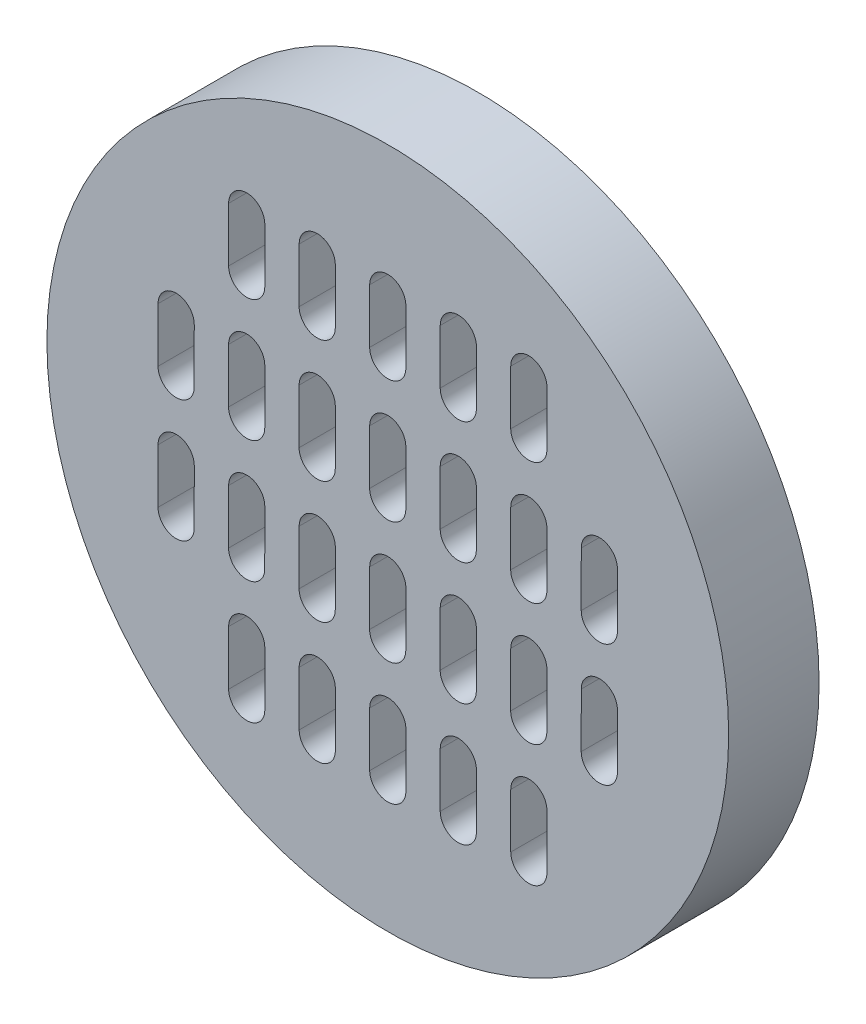
SolidWorks part; units mm, degrees
ref_plane "Спереди" through (0, 0, 0) normal (0, 0, 1) x (1, 0, 0)
ref_plane "Сверху" through (0, 0, 0) normal (0, 1, 0) x (1, 0, 0)
ref_plane "Справа" through (0, 0, 0) normal (1, 0, 0) x (0, 0, -1)
sketch "Sketch1" plane through (0, 0, 0) normal (0, 0, 1) x (1, 0, 0)
  line L0 (3.9, 6.755) -> (7.8, 0) construction
  line L2 (5.85, 10.1325) -> (11.7, 0) construction
  line L4 (7.8, 13.51) -> (15.6, 0) construction
  circle A61 centre (0, 0) radius 20
  circle A131 centre (0, 0) radius 1.25
  circle A484 centre (3.9, 0) radius 1.25
  circle A485 centre (7.8, 0) radius 1.25
  circle A486 centre (11.7, 0) radius 1.25
  circle A487 centre (15.6, 0) radius 1.25
  circle A488 centre (1.95, -3.3775) radius 1.25
  circle A489 centre (3.9, -6.755) radius 1.25
  circle A490 centre (5.85, -10.1325) radius 1.25
  circle A491 centre (7.8, -13.51) radius 1.25
  circle A492 centre (-1.95, -3.3775) radius 1.25
  circle A493 centre (-3.9, -6.755) radius 1.25
  circle A494 centre (-5.85, -10.1325) radius 1.25
  circle A495 centre (-7.8, -13.51) radius 1.25
  circle A496 centre (-3.9, 0) radius 1.25
  circle A497 centre (-7.8, 0) radius 1.25
  circle A498 centre (-11.7, 0) radius 1.25
  circle A499 centre (-15.6, 0) radius 1.25
  circle A500 centre (-1.95, 3.3775) radius 1.25
  circle A501 centre (-3.9, 6.755) radius 1.25
  circle A502 centre (-5.85, 10.1325) radius 1.25
  circle A503 centre (-7.8, 13.51) radius 1.25
  circle A504 centre (1.95, 3.3775) radius 1.25
  circle A505 centre (3.9, 6.755) radius 1.25
  circle A506 centre (5.85, 10.1325) radius 1.25
  circle A507 centre (7.8, 13.51) radius 1.25
  circle A508 centre (5.85, 3.3775) radius 1.25
  circle A509 centre (7.8, 6.755) radius 1.25
  circle A510 centre (9.75, 3.3775) radius 1.25
  circle A511 centre (11.7, 6.755) radius 1.25
  circle A512 centre (9.7491, 10.1341) radius 1.25
  circle A513 centre (13.6509, 3.3759) radius 1.25
  circle A514 centre (5.85, -3.3791) radius 1.25
  circle A515 centre (9.75, -3.3791) radius 1.25
  circle A516 centre (7.8, -6.7566) radius 1.25
  circle A517 centre (11.7, -6.7566) radius 1.25
  circle A518 centre (9.7491, -10.1356) radius 1.25
  circle A519 centre (13.6509, -3.3775) radius 1.25
  circle A520 centre (-0.0013, -6.7573) radius 1.25
  circle A521 centre (1.9487, -10.1348) radius 1.25
  circle A522 centre (-1.9513, -10.1348) radius 1.25
  circle A523 centre (-0.0013, -13.5123) radius 1.25
  circle A524 centre (-3.9032, -13.5123) radius 1.25
  circle A525 centre (3.9005, -13.5123) radius 1.25
  circle A526 centre (-5.8527, -3.3791) radius 1.25
  circle A527 centre (-7.8027, -6.7566) radius 1.25
  circle A528 centre (-9.7527, -3.3791) radius 1.25
  circle A529 centre (-11.7027, -6.7566) radius 1.25
  circle A530 centre (-13.6536, -3.3775) radius 1.25
  circle A531 centre (-9.7518, -10.1356) radius 1.25
  circle A532 centre (-5.8527, 3.3775) radius 1.25
  circle A533 centre (-9.7527, 3.3775) radius 1.25
  circle A534 centre (-7.8027, 6.755) radius 1.25
  circle A535 centre (-11.7027, 6.755) radius 1.25
  circle A536 centre (-9.7518, 10.1341) radius 1.25
  circle A537 centre (-13.6536, 3.3759) radius 1.25
  circle A538 centre (-0.0014, 6.7558) radius 1.25
  circle A539 centre (-1.9514, 10.1333) radius 1.25
  circle A540 centre (1.9486, 10.1333) radius 1.25
  circle A541 centre (-0.0014, 13.5108) radius 1.25
  circle A542 centre (3.9005, 13.5108) radius 1.25
  circle A543 centre (-3.9032, 13.5108) radius 1.25
  circle A544 centre (13.65, -1.1258) radius 2.2517 construction
  circle A545 centre (11.7009, -4.5044) radius 2.2522 construction
  circle A546 centre (9.75, -7.8834) radius 2.2522 construction
  circle A547 centre (7.7987, -11.2591) radius 2.2509 construction
  circle A548 centre (13.65, -1.1258) radius 0.65
  circle A549 centre (11.7009, -4.5044) radius 0.65
  circle A550 centre (9.75, -7.8834) radius 0.65
  circle A551 centre (7.7987, -11.2591) radius 0.65
  circle A552 centre (9.75, -1.1258) radius 0.65
  circle A553 centre (7.8009, -4.5044) radius 0.65
  circle A554 centre (5.85, -7.8834) radius 0.65
  circle A555 centre (3.8987, -11.2591) radius 0.65
  circle A556 centre (5.85, -1.1258) radius 0.65
  circle A557 centre (3.9009, -4.5044) radius 0.65
  circle A558 centre (1.95, -7.8834) radius 0.65
  circle A559 centre (-0.0013, -11.2591) radius 0.65
  circle A560 centre (1.95, -1.1258) radius 0.65
  circle A561 centre (0.0009, -4.5044) radius 0.65
  circle A562 centre (-1.95, -7.8834) radius 0.65
  circle A563 centre (-3.9013, -11.2591) radius 0.65
  circle A564 centre (-1.95, -1.1258) radius 0.65
  circle A565 centre (-3.8991, -4.5044) radius 0.65
  circle A566 centre (-5.85, -7.8834) radius 0.65
  circle A567 centre (-7.8013, -11.2591) radius 0.65
  circle A568 centre (-5.85, -1.1258) radius 0.65
  circle A569 centre (-7.7991, -4.5044) radius 0.65
  circle A570 centre (-9.75, -7.8834) radius 0.65
  circle A572 centre (-9.75, -1.1258) radius 0.65
  circle A573 centre (-11.6991, -4.5044) radius 0.65
  circle A576 centre (-13.65, -1.1258) radius 0.65
  circle A587 centre (0, 2.2517) radius 2.2517 construction
  circle A588 centre (0, 2.2517) radius 0.65
  circle A589 centre (3.9, 2.2517) radius 0.65
  circle A590 centre (7.8, 2.2517) radius 0.65
  circle A591 centre (11.7, 2.2517) radius 0.65
  circle A592 centre (15.6, 2.2517) radius 0.65
  circle A593 centre (1.9491, 5.6297) radius 2.2522 construction
  circle A594 centre (1.9491, 5.6297) radius 0.65
  circle A595 centre (5.8491, 5.6297) radius 0.65
  circle A596 centre (9.7491, 5.6297) radius 0.65
  circle A597 centre (13.6491, 5.6297) radius 0.65
  circle A598 centre (3.8991, 9.0072) radius 2.2522 construction
  circle A599 centre (3.8991, 9.0072) radius 0.65
  circle A600 centre (7.7991, 9.0072) radius 0.65
  circle A601 centre (11.6991, 9.0072) radius 0.65
  circle A602 centre (5.85, 12.3842) radius 2.2517 construction
  circle A603 centre (5.85, 12.3842) radius 0.65
  circle A604 centre (9.75, 12.3842) radius 0.65
  circle A605 centre (5.85, -14.6358) radius 0.65
  circle A606 centre (1.9509, -14.6353) radius 0.65
  circle A607 centre (-1.9491, -14.6353) radius 0.65
  circle A608 centre (-5.85, -14.6358) radius 0.65
  circle A609 centre (-15.6, 2.2517) radius 0.65
  circle A610 centre (-13.65, 5.6281) radius 0.65
  circle A611 centre (-11.7, 9.0056) radius 0.65
  circle A612 centre (-9.75, 12.3842) radius 0.65
  circle A613 centre (-5.85, 12.3842) radius 0.65
  circle A614 centre (-1.95, 12.3842) radius 0.65
  circle A615 centre (1.95, 12.3842) radius 0.65
  circle A616 centre (-7.8, 9.0056) radius 0.65
  circle A617 centre (-9.75, 5.6281) radius 0.65
  circle A618 centre (-11.7, 2.2517) radius 0.65
  circle A619 centre (-3.9, 9.0056) radius 0.65
  circle A620 centre (-5.85, 5.6281) radius 0.65
  circle A621 centre (-7.8, 2.2517) radius 0.65
  circle A622 centre (0, 9.0056) radius 0.65
  circle A623 centre (-1.95, 5.6281) radius 0.65
  circle A624 centre (-3.9, 2.2517) radius 0.65
  circle A625 centre (-15.5991, -4.5044) radius 0.65
  circle A626 centre (-13.65, -7.8834) radius 0.65
  circle A627 centre (-17.55, -7.8834) radius 0.65
  circle A628 centre (-19.5013, -11.2591) radius 0.65
  circle A629 centre (-15.6013, -11.2591) radius 0.65
  circle A630 centre (-11.7013, -11.2591) radius 0.65
  point P51 (0, 0)
  point P125 (-0.0013, -0.0008)
  point P214 (0, 0)
  point P231 (0, 0)
  dimension "D1" = 5
  dimension "D3" = 6
  dimension "D5" = 8
  dimension "D7" = 4
  dimension "D11" = 4
  dimension "D2" = 6
  dimension "D6" = 5
  dimension "D8" = 3
  dimension "D9" = 2
  dimension "D4" = 1.3
  dimension "D10" = 3
ref_plane "Plane1" through (0, 0, 10) normal (0, 0, 1) x (1, 0, 0)
sketch "Sketch2" plane through (0, 0, 10) normal (0, 0, 1) x (1, 0, 0)
  line L0 (-7.8, 13.51) -> (-7.8027, 6.755) construction
  line L1 (-9.7518, 10.1341) -> (-5.85, 10.1325) construction
  line L2 (-7.8008, 11.6325) -> (-7.8019, 8.6325) construction
  line L3 (-6.8008, 11.6321) -> (-6.8019, 8.6321)
  line L4 (-8.8008, 11.6329) -> (-8.8019, 8.6329)
  line L5 (-4.9008, 11.6329) -> (-4.9019, 8.6329)
  line L6 (-2.9008, 11.6321) -> (-2.9019, 8.6321)
  line L7 (-3.9008, 11.6325) -> (-3.9019, 8.6325) construction
  line L8 (-1.0008, 11.6329) -> (-1.0019, 8.6329)
  line L9 (0.9992, 11.6321) -> (0.9981, 8.6321)
  line L10 (-0.0008, 11.6325) -> (-0.0019, 8.6325) construction
  line L11 (2.8992, 11.6329) -> (2.8981, 8.6329)
  line L12 (4.8992, 11.6321) -> (4.8981, 8.6321)
  line L13 (3.8992, 11.6325) -> (3.8981, 8.6325) construction
  line L14 (6.7992, 11.6329) -> (6.7981, 8.6329)
  line L15 (8.7992, 11.6321) -> (8.7981, 8.6321)
  line L16 (7.7992, 11.6325) -> (7.7981, 8.6325) construction
  line L17 (-9.7518, 10.1341) -> (-9.7527, 3.3775) construction
  line L18 (-11.7027, 6.755) -> (-7.8027, 6.755) construction
  line L19 (-10.7035, 1.877) -> (-10.702, 4.877)
  line L22 (-9.7527, 3.3775) -> (-5.8527, 3.3775) construction
  line L25 (-7.8027, 6.755) -> (-7.8, 0) construction
  line L26 (-7.8035, 1.8775) -> (-7.8019, 4.8775) construction
  line L27 (-8.8035, 1.878) -> (-8.8019, 4.878)
  line L28 (-6.8035, 1.877) -> (-6.8019, 4.877)
  line L29 (-2.9035, 1.877) -> (-2.9019, 4.877)
  line L30 (-4.9035, 1.878) -> (-4.9019, 4.878)
  line L31 (-3.9035, 1.8775) -> (-3.9019, 4.8775) construction
  line L32 (0.9965, 1.877) -> (0.9981, 4.877)
  line L33 (-1.0035, 1.878) -> (-1.0019, 4.878)
  line L34 (-0.0035, 1.8775) -> (-0.0019, 4.8775) construction
  line L35 (4.8965, 1.877) -> (4.8981, 4.877)
  line L36 (2.8965, 1.878) -> (2.8981, 4.878)
  line L37 (3.8965, 1.8775) -> (3.8981, 4.8775) construction
  line L38 (8.7965, 1.877) -> (8.7981, 4.877)
  line L39 (6.7965, 1.878) -> (6.7981, 4.878)
  line L40 (7.7965, 1.8775) -> (7.7981, 4.8775) construction
  line L41 (12.6965, 1.877) -> (12.6981, 4.877)
  line L42 (10.6965, 1.878) -> (10.6981, 4.878)
  line L43 (11.6965, 1.8775) -> (11.6981, 4.8775) construction
  line L44 (-12.7035, 1.878) -> (-12.7019, 4.878)
  line L45 (-11.7035, 1.8775) -> (-11.702, 4.8775) construction
  line L46 (-9.7527, -3.3791) -> (-5.8527, -3.3791) construction
  line L47 (-7.8, 0) -> (-7.8027, -6.7566) construction
  line L48 (-7.8046, -4.8791) -> (-7.8008, -1.8791) construction
  line L49 (-8.8046, -4.8778) -> (-8.8008, -1.8778)
  line L50 (-6.8046, -4.8804) -> (-6.8008, -1.8804)
  line L51 (-2.9046, -4.8804) -> (-2.9008, -1.8804)
  line L52 (-4.9046, -4.8778) -> (-4.9008, -1.8778)
  line L53 (-3.9046, -4.8791) -> (-3.9008, -1.8791) construction
  line L54 (0.9954, -4.8804) -> (0.9992, -1.8804)
  line L55 (-1.0046, -4.8778) -> (-1.0008, -1.8778)
  line L56 (-0.0046, -4.8791) -> (-0.0008, -1.8791) construction
  line L57 (4.8954, -4.8804) -> (4.8992, -1.8804)
  line L58 (2.8954, -4.8778) -> (2.8992, -1.8778)
  line L59 (3.8954, -4.8791) -> (3.8992, -1.8791) construction
  line L60 (8.7954, -4.8804) -> (8.7992, -1.8804)
  line L61 (6.7954, -4.8778) -> (6.7992, -1.8778)
  line L62 (7.7954, -4.8791) -> (7.7992, -1.8791) construction
  line L63 (12.6954, -4.8804) -> (12.6992, -1.8804)
  line L64 (10.6954, -4.8778) -> (10.6992, -1.8778)
  line L65 (11.6954, -4.8791) -> (11.6992, -1.8791) construction
  line L66 (-10.7046, -4.8804) -> (-10.7008, -1.8804)
  line L67 (-12.7046, -4.8778) -> (-12.7008, -1.8778)
  line L68 (-11.7046, -4.8791) -> (-11.7008, -1.8791) construction
  line L69 (-9.7518, -10.1356) -> (-5.482, -10.1356) construction
  line L70 (-7.8027, -6.7566) -> (-7.8, -13.51) construction
  line L71 (-7.8007, -8.6356) -> (-7.8007, -11.6356) construction
  line L72 (-6.8007, -8.6356) -> (-6.8007, -11.6356)
  line L73 (-8.8007, -8.6356) -> (-8.8007, -11.6356)
  line L74 (-4.9007, -8.6356) -> (-4.9007, -11.6356)
  line L75 (-2.9007, -8.6356) -> (-2.9007, -11.6356)
  line L76 (-3.9007, -8.6356) -> (-3.9007, -11.6356) construction
  line L77 (-1.0007, -8.6356) -> (-1.0007, -11.6356)
  line L78 (0.9993, -8.6356) -> (0.9993, -11.6356)
  line L79 (-0.0007, -8.6356) -> (-0.0007, -11.6356) construction
  line L80 (2.8993, -8.6356) -> (2.8993, -11.6356)
  line L81 (4.8993, -8.6356) -> (4.8993, -11.6356)
  line L82 (3.8993, -8.6356) -> (3.8993, -11.6356) construction
  line L83 (6.7993, -8.6356) -> (6.7993, -11.6356)
  line L84 (8.7993, -8.6356) -> (8.7993, -11.6356)
  line L85 (7.7993, -8.6356) -> (7.7993, -11.6356) construction
  arc A0 (-6.8008, 11.6321) -> (-8.8008, 11.6329) centre (-7.8008, 11.6325) ccw
  arc A1 (-8.8019, 8.6329) -> (-6.8019, 8.6321) centre (-7.8019, 8.6325) ccw
  arc A2 (-2.9008, 11.6321) -> (-4.9008, 11.6329) centre (-3.9008, 11.6325) ccw
  arc A3 (-4.9019, 8.6329) -> (-2.9019, 8.6321) centre (-3.9019, 8.6325) ccw
  arc A4 (0.9992, 11.6321) -> (-1.0008, 11.6329) centre (-0.0008, 11.6325) ccw
  arc A5 (-1.0019, 8.6329) -> (0.9981, 8.6321) centre (-0.0019, 8.6325) ccw
  arc A6 (4.8992, 11.6321) -> (2.8992, 11.6329) centre (3.8992, 11.6325) ccw
  arc A7 (2.8981, 8.6329) -> (4.8981, 8.6321) centre (3.8981, 8.6325) ccw
  arc A8 (8.7992, 11.6321) -> (6.7992, 11.6329) centre (7.7992, 11.6325) ccw
  arc A9 (6.7981, 8.6329) -> (8.7981, 8.6321) centre (7.7981, 8.6325) ccw
  arc A14 (-8.8035, 1.878) -> (-6.8035, 1.877) centre (-7.8035, 1.8775) ccw
  arc A15 (-6.8019, 4.877) -> (-8.8019, 4.878) centre (-7.8019, 4.8775) ccw
  arc A16 (-4.9035, 1.878) -> (-2.9035, 1.877) centre (-3.9035, 1.8775) ccw
  arc A17 (-2.9019, 4.877) -> (-4.9019, 4.878) centre (-3.9019, 4.8775) ccw
  arc A18 (-1.0035, 1.878) -> (0.9965, 1.877) centre (-0.0035, 1.8775) ccw
  arc A19 (0.9981, 4.877) -> (-1.0019, 4.878) centre (-0.0019, 4.8775) ccw
  arc A20 (2.8965, 1.878) -> (4.8965, 1.877) centre (3.8965, 1.8775) ccw
  arc A21 (4.8981, 4.877) -> (2.8981, 4.878) centre (3.8981, 4.8775) ccw
  arc A22 (6.7965, 1.878) -> (8.7965, 1.877) centre (7.7965, 1.8775) ccw
  arc A23 (8.7981, 4.877) -> (6.7981, 4.878) centre (7.7981, 4.8775) ccw
  arc A24 (10.6965, 1.878) -> (12.6965, 1.877) centre (11.6965, 1.8775) ccw
  arc A25 (12.6981, 4.877) -> (10.6981, 4.878) centre (11.6981, 4.8775) ccw
  arc A26 (-12.7035, 1.878) -> (-10.7035, 1.877) centre (-11.7035, 1.8775) ccw
  arc A27 (-10.702, 4.877) -> (-12.7019, 4.878) centre (-11.702, 4.8775) ccw
  arc A28 (-8.8046, -4.8778) -> (-6.8046, -4.8804) centre (-7.8046, -4.8791) ccw
  arc A29 (-6.8008, -1.8804) -> (-8.8008, -1.8778) centre (-7.8008, -1.8791) ccw
  arc A30 (-4.9046, -4.8778) -> (-2.9046, -4.8804) centre (-3.9046, -4.8791) ccw
  arc A31 (-2.9008, -1.8804) -> (-4.9008, -1.8778) centre (-3.9008, -1.8791) ccw
  arc A32 (-1.0046, -4.8778) -> (0.9954, -4.8804) centre (-0.0046, -4.8791) ccw
  arc A33 (0.9992, -1.8804) -> (-1.0008, -1.8778) centre (-0.0008, -1.8791) ccw
  arc A34 (2.8954, -4.8778) -> (4.8954, -4.8804) centre (3.8954, -4.8791) ccw
  arc A35 (4.8992, -1.8804) -> (2.8992, -1.8778) centre (3.8992, -1.8791) ccw
  arc A36 (6.7954, -4.8778) -> (8.7954, -4.8804) centre (7.7954, -4.8791) ccw
  arc A37 (8.7992, -1.8804) -> (6.7992, -1.8778) centre (7.7992, -1.8791) ccw
  arc A38 (10.6954, -4.8778) -> (12.6954, -4.8804) centre (11.6954, -4.8791) ccw
  arc A39 (12.6992, -1.8804) -> (10.6992, -1.8778) centre (11.6992, -1.8791) ccw
  arc A40 (-12.7046, -4.8778) -> (-10.7046, -4.8804) centre (-11.7046, -4.8791) ccw
  arc A41 (-10.7008, -1.8804) -> (-12.7008, -1.8778) centre (-11.7008, -1.8791) ccw
  arc A42 (-6.8007, -8.6356) -> (-8.8007, -8.6356) centre (-7.8007, -8.6356) ccw
  arc A43 (-8.8007, -11.6356) -> (-6.8007, -11.6356) centre (-7.8007, -11.6356) ccw
  arc A44 (-2.9007, -8.6356) -> (-4.9007, -8.6356) centre (-3.9007, -8.6356) ccw
  arc A45 (-4.9007, -11.6356) -> (-2.9007, -11.6356) centre (-3.9007, -11.6356) ccw
  arc A46 (0.9993, -8.6356) -> (-1.0007, -8.6356) centre (-0.0007, -8.6356) ccw
  arc A47 (-1.0007, -11.6356) -> (0.9993, -11.6356) centre (-0.0007, -11.6356) ccw
  arc A48 (4.8993, -8.6356) -> (2.8993, -8.6356) centre (3.8993, -8.6356) ccw
  arc A49 (2.8993, -11.6356) -> (4.8993, -11.6356) centre (3.8993, -11.6356) ccw
  arc A50 (8.7993, -8.6356) -> (6.7993, -8.6356) centre (7.7993, -8.6356) ccw
  arc A51 (6.7993, -11.6356) -> (8.7993, -11.6356) centre (7.7993, -11.6356) ccw
  circle A52 centre (0, 0) radius 16.85 construction
  circle A53 centre (0, 0) radius 18.85
  point P10 (-7.8014, 10.1325)
  point P18 (-3.9014, 10.1325)
  point P25 (-0.0014, 10.1325)
  point P32 (3.8986, 10.1325)
  point P39 (7.7986, 10.1325)
  point P50 (-11.7027, 3.3775)
  point P58 (-7.8027, 3.3775)
  point P68 (-3.9027, 3.3775)
  point P75 (-0.0027, 3.3775)
  point P82 (3.8973, 3.3775)
  point P89 (7.7973, 3.3775)
  point P96 (11.6973, 3.3775)
  point P108 (-7.8027, -3.3791)
  point P116 (-3.9027, -3.3791)
  point P123 (-0.0027, -3.3791)
  point P130 (3.8973, -3.3791)
  point P137 (7.7973, -3.3791)
  point P144 (11.6973, -3.3791)
  point P151 (-11.7027, -3.3791)
  point P162 (-7.8007, -10.1356)
  point P170 (-3.9007, -10.1356)
  point P177 (-0.0007, -10.1356)
  point P184 (3.8993, -10.1356)
  point P191 (7.7993, -10.1356)
  dimension "D1" = 2
  dimension "D15" = 2
  dimension "D2" = 3
  dimension "D4" = 2
  dimension "D5" = 3
  dimension "D6" = 2
  dimension "D7" = 3
  dimension "D9" = 2
  dimension "D12" = 3
  dimension "D13" = 2
  dimension "D3" = 5
  dimension "D8" = 6
  dimension "D10" = 6
  dimension "D11" = 2
  dimension "D14" = 5
extrude "Boss-Extrude1" add sketch "Sketch2" along normal blind 5
